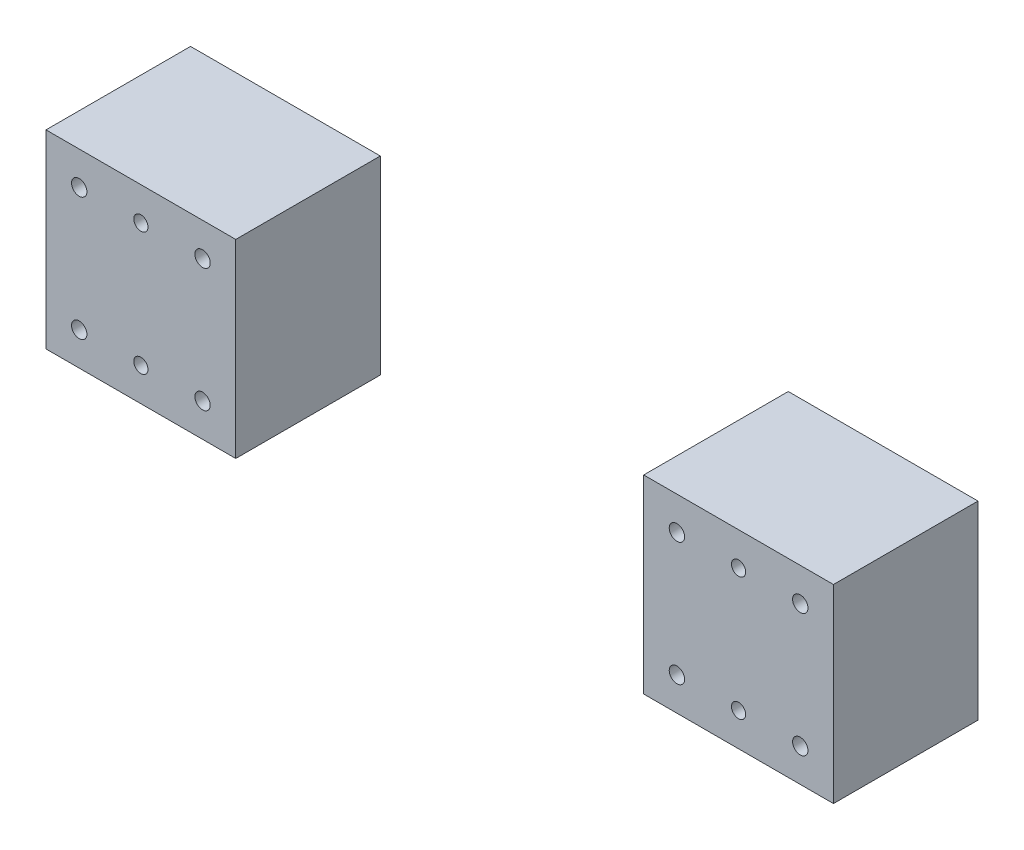
SolidWorks part; units mm, degrees
ref_plane "Front Plane" through (0, 0, 0) normal (0, 0, 1) x (1, 0, 0)
ref_plane "Top Plane" through (0, 0, 0) normal (0, 1, 0) x (1, 0, 0)
ref_plane "Right Plane" through (0, 0, 0) normal (1, 0, 0) x (0, 0, -1)
sketch "Sketch1" plane through (0, 0, 0) normal (0, 0, 1) x (-1, 0, 0)
  line L1 (0, 0) -> (-40, 0)
  line L2 (0, 0) -> (0, -40)
  line L3 (0, -40) -> (-40, -40)
  line L4 (-40, 0) -> (-40, -40)
  line L5 (-126, 0) -> (-166, 0)
  line L6 (-126, 0) -> (-126, -40)
  line L7 (-126, -40) -> (-166, -40)
  line L8 (-166, 0) -> (-166, -40)
  circle A8 centre (-159, -7) radius 1.621
  circle A9 centre (-133, -7) radius 1.621
  circle A10 centre (-133, -33) radius 1.621
  circle A11 centre (-159, -33) radius 1.621
  circle A12 centre (-33, -7) radius 1.621
  circle A13 centre (-7, -7) radius 1.621
  circle A14 centre (-7, -33) radius 1.621
  circle A15 centre (-33, -33) radius 1.621
  dimension "D25" = 3.242
  dimension "D26" = 3.242
  dimension "D27" = 3.242
  dimension "D28" = 3.242
  dimension "D29" = 3.242
  dimension "D30" = 3.242
  dimension "D31" = 3.242
  dimension "D32" = 3.242
  dimension "D1" = 26
  dimension "D2" = 26
  dimension "D3" = 26
  dimension "D4" = 26
  dimension "D5" = 40
  dimension "D6" = 40
  dimension "D7" = 7
  dimension "D8" = 7
  dimension "D9" = 7
  dimension "D10" = 100
  dimension "D11" = 26
  dimension "D12" = 26
  dimension "D13" = 100
  dimension "D14" = 26
  dimension "D15" = 26
  dimension "D16" = 40
  dimension "D17" = 40
  dimension "D18" = 7
  dimension "D19" = 7
  dimension "D20" = 7
  dimension "D21" = 0
  dimension "D22" = 0
  dimension "D23" = 40
  dimension "D24" = 0
extrude "Boss-Extrude1" add sketch "Sketch1" along normal blind 30.47
sketch "Sketch4" plane through (0, 0, 0) normal (0, 0, -1) x (-1, 0, 0)
  circle A8 centre (-7, 7) radius 4.2
  circle A9 centre (-33, 7) radius 4.2
  circle A10 centre (-7, 33) radius 4.2
  circle A11 centre (-33, 33) radius 4.2
  circle A12 centre (-133, 7) radius 4.2
  circle A13 centre (-133, 33) radius 4.2
  circle A14 centre (-159, 33) radius 4.2
  circle A15 centre (-159, 7) radius 4.2
extrude "Cut-Extrude1" cut sketch "Sketch4" against normal blind 20
sketch "Sketch5" plane through (0, 0, 0) normal (0, 0, -1) x (-1, 0, 0)
  line L0 (0, 40) -> (0, 0) construction
  line L1 (-40, 40) -> (0, 40) construction
  line L2 (-126, 40) -> (-126, 0) construction
  line L3 (-166, 40) -> (-126, 40) construction
  circle A0 centre (-20, 7) radius 1.5
  circle A1 centre (-20, 33) radius 1.5
  circle A2 centre (-146, 7) radius 1.5
  circle A3 centre (-146, 33) radius 1.5
  dimension "D1" = 3
  dimension "D2" = 3
  dimension "D3" = 3
  dimension "D4" = 3
  dimension "D7" = 7
  dimension "D5" = 20
  dimension "D6" = 26
  dimension "D8" = 20
  dimension "D9" = 26
  dimension "D10" = 7
extrude "Cut-Extrude2" cut sketch "Sketch5" against normal through all
